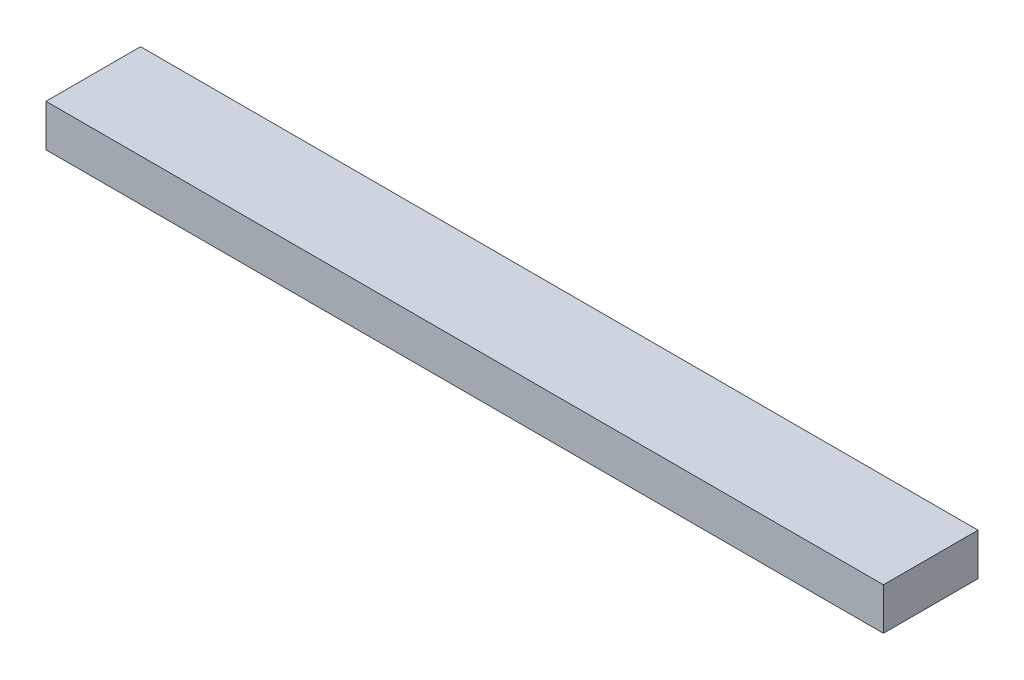
SolidWorks part; units mm, degrees
material "MDF"
ref_plane "Front Plane" through (0, 0, 0) normal (0, 0, 1) x (1, 0, 0)
ref_plane "Top Plane" through (0, 0, 0) normal (0, 1, 0) x (1, 0, 0)
ref_plane "Right Plane" through (0, 0, 0) normal (1, 0, 0) x (0, 0, -1)
sketch "Sketch1" plane through (0, 0, 0) normal (0, 0, 1) x (1, 0, 0)
  line L0 (0, -659.4362) -> (0, 659.4362) construction
  line L1 (-126.4888, -311.15) -> (126.4888, -311.15)
  line L2 (-126.4888, -311.15) -> (-126.4888, -298.45)
  line L3 (-126.4888, -298.45) -> (126.4888, -298.45)
  line L4 (0, -311.15) -> (0, -298.45) construction
  line L5 (126.4888, -311.15) -> (126.4888, -298.45)
  dimension "D1" = 12.7
extrude "Boss-Extrude1" add sketch "Sketch1" along normal up to surface (28.575 mm away)
